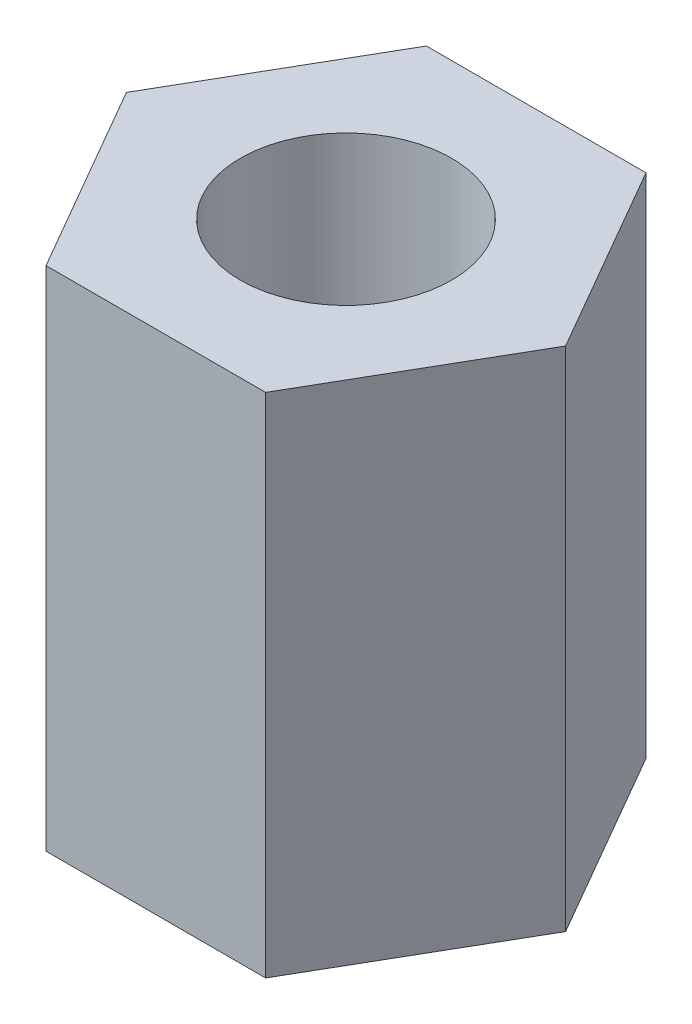
SolidWorks part; units mm, degrees
material "ABS"
ref_plane "前视基准面" through (0, 0, 0) normal (0, 0, 1) x (1, 0, 0)
ref_plane "上视基准面" through (0, 0, 0) normal (0, 1, 0) x (1, 0, 0)
ref_plane "右视基准面" through (0, 0, 0) normal (1, 0, 0) x (0, 0, -1)
sketch "草图1" plane through (0, 0, 0) normal (0, 1, 0) x (1, 0, 0)
  line L1 (1.299, -2.25) -> (2.5981, 0)
  line L2 (2.5981, 0) -> (1.299, 2.25)
  line L3 (1.299, 2.25) -> (-1.299, 2.25)
  line L4 (-1.299, 2.25) -> (-2.5981, 0)
  line L5 (-2.5981, 0) -> (-1.299, -2.25)
  line L6 (-1.299, -2.25) -> (1.299, -2.25)
  circle A0 centre (0, 0) radius 1.25
  circle A1 centre (0, 0) radius 2.25 construction
  dimension "D1" = 2.5
  dimension "D2" = 4.5
extrude "凸台-拉伸1" add sketch "草图1" along normal blind 6
